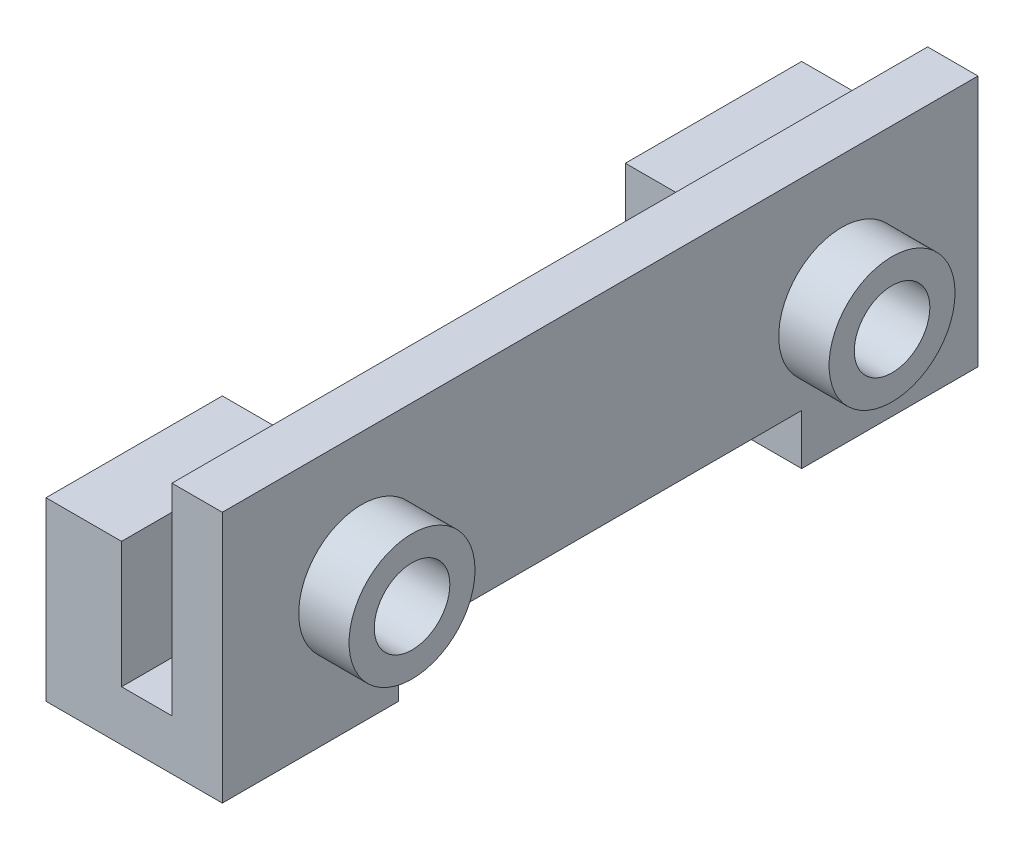
SolidWorks part; units mm, degrees
ref_plane "Front Plane" through (0, 0, 0) normal (0, 0, 1) x (1, 0, 0)
ref_plane "Top Plane" through (0, 0, 0) normal (0, 1, 0) x (1, 0, 0)
ref_plane "Right Plane" through (0, 0, 0) normal (1, 0, 0) x (0, 0, -1)
sketch "Esquisse1" plane through (0, 0, 0) normal (1, 0, 0) x (0, 0, -1)
  line L1 (-15, 5) -> (15, 5)
  line L2 (-15, 5) -> (-15, -5)
  line L3 (-15, -5) -> (15, -5)
  line L4 (15, 5) -> (15, -5)
  line L5 (-15, 5) -> (15, -5) construction
  line L6 (-15, -5) -> (15, 5) construction
  point P0 (0, 0)
  point P6 (0, 0)
extrude "Boss.-Extru.1" add sketch "Esquisse1" along normal blind 2
sketch "Esquisse2" plane through (2, 0, 0) normal (1, 0, 0) x (0, 0, -1)
  line L0 (-15, -5) -> (15, -5) construction
  circle A0 centre (-9.4678, 0) radius 2.5
  circle A1 centre (9.5886, 0) radius 2.5
  dimension "D1" = 5
extrude "Boss.-Extru.2" add sketch "Esquisse2" along normal blind 2 contours A1 | A0
sketch "Esquisse3" plane through (4, 0, 0) normal (1, 0, 0) x (0, 0, -1)
  circle A0 centre (-9.4678, 0) radius 1.5
extrude "Enlèv. mat.-Extru.1" cut sketch "Esquisse3" against normal through all contours A0
sketch "Esquisse4" plane through (4, 0, 0) normal (1, 0, 0) x (0, 0, -1)
  circle A0 centre (9.5886, 0) radius 1.5
extrude "Enlèv. mat.-Extru.2" cut sketch "Esquisse4" against normal through all
ref_plane "Plan1" through (0, 0, 0) normal (0, 0, 1) x (1, 0, 0)
sketch "Esquisse7" plane through (0, -5, 0) normal (0, -1, 0) x (1, 0, 0)
  line L0 (0, 0) -> (2, 0) construction
  line L1 (0, 15) -> (0, -15) construction
  line L2 (2, 15) -> (2, -15) construction
  line L4 (0, 8) -> (2, 8)
  line L5 (0, 8) -> (0, 0)
  line L6 (0, 0) -> (2, 0)
  line L7 (2, 8) -> (2, 0)
extrude "Enlèv. mat.-Extru.3" cut sketch "Esquisse7" against normal blind 2
mirror "Symétrie1" about plane through (0, 0, 0) normal (0, 0, 1) of "Enlèv. mat.-Extru.3"
sketch "Esquisse8" plane through (0, 0, 0) normal (-1, 0, 0) x (0, 0, 1)
  line L1 (-15, -5) -> (-8, -5)
  line L2 (-15, -5) -> (-15, -3)
  line L3 (-15, -3) -> (-8, -3)
  line L4 (-8, -5) -> (-8, -3)
extrude "Boss.-Extru.3" add sketch "Esquisse8" along normal blind 5
sketch "Esquisse12" plane through (0, -3, 0) normal (0, 1, 0) x (1, 0, 0)
  line L0 (-5, 8) -> (0, 8) construction
  line L1 (-5, 15) -> (-2, 15)
  line L2 (-5, 15) -> (-5, 8)
  line L3 (-5, 8) -> (-2, 8)
  line L4 (-2, 15) -> (-2, 8)
extrude "Boss.-Extru.4" add sketch "Esquisse12" along normal blind 5
mirror "Symétrie2" about plane through (0, 0, 0) normal (0, 0, 1) of "Boss.-Extru.4", "Boss.-Extru.3"
